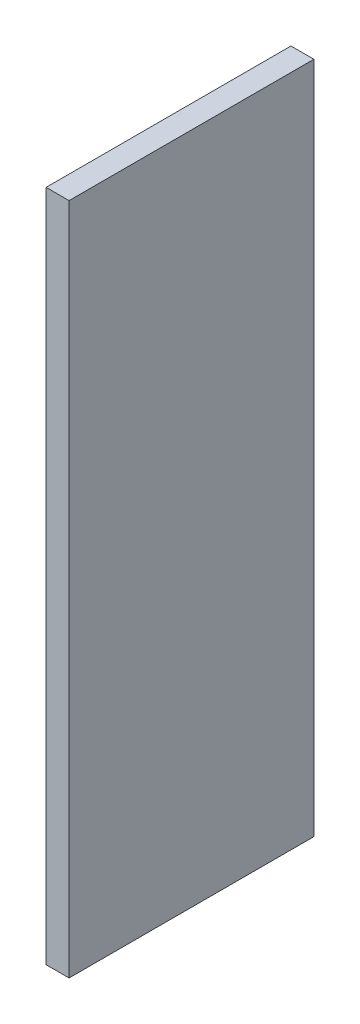
SolidWorks part; units mm, degrees
ref_plane "Front Plane" through (0, 0, 0) normal (0, 0, 1) x (1, 0, 0)
ref_plane "Top Plane" through (0, 0, 0) normal (0, 1, 0) x (1, 0, 0)
ref_plane "Right Plane" through (0, 0, 0) normal (1, 0, 0) x (0, 0, -1)
sketch "Sketch1" plane through (0, 0, 0) normal (1, 0, 0) x (0, 0, -1)
  line L1 (-30.4666, 510.8196) -> (172.7334, 510.8196)
  line L2 (-30.4666, 510.8196) -> (-30.4666, -47.9804)
  line L3 (-30.4666, -47.9804) -> (172.7334, -47.9804)
  line L4 (172.7334, 510.8196) -> (172.7334, -47.9804)
extrude "Boss-Extrude1" add sketch "Sketch1" along normal blind 19.05 contours L2 L1 L4 L3
